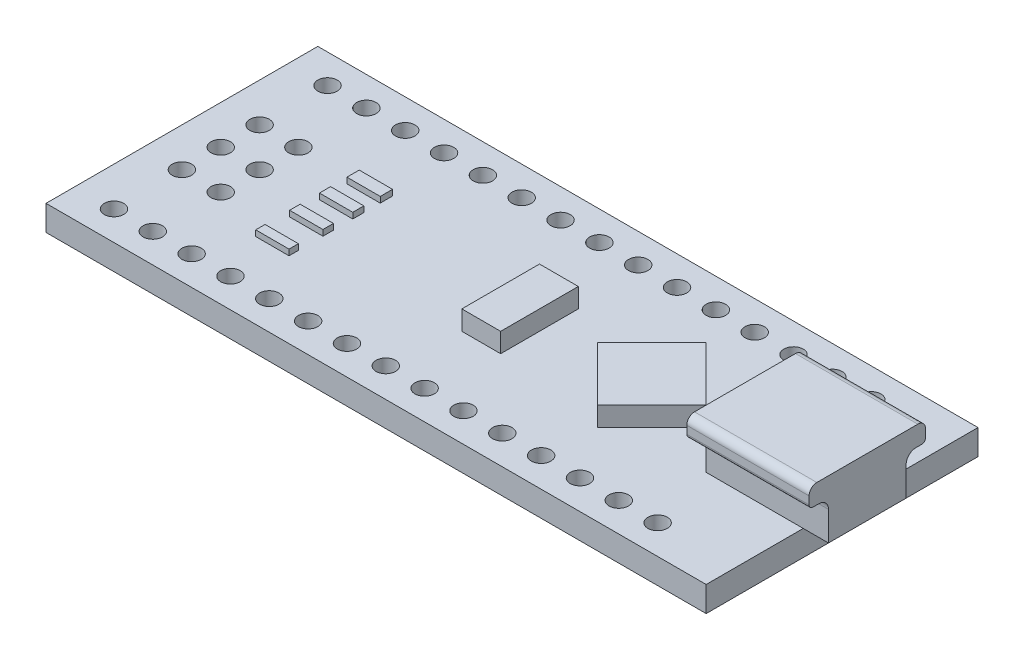
SolidWorks part; units mm, degrees
ref_plane "Front Plane" through (0, 0, 0) normal (0, 0, 1) x (1, 0, 0)
ref_plane "Top Plane" through (0, 0, 0) normal (0, 1, 0) x (1, 0, 0)
ref_plane "Right Plane" through (0, 0, 0) normal (1, 0, 0) x (0, 0, -1)
sketch "Sketch1" plane through (0, 0, 0) normal (0, 1, 0) x (1, 0, 0)
  line L1 (0, 0) -> (43.18, 0)
  line L2 (0, 0) -> (0, 17.78)
  line L3 (0, 17.78) -> (43.18, 17.78)
  line L4 (43.18, 0) -> (43.18, 17.78)
  dimension "D1" = 17.78
  dimension "D2" = 43.18
extrude "Boss-Extrude1" add sketch "Sketch1" along normal blind 1.651
sketch "Sketch2" plane through (0, 1.651, 0) normal (0, 1, 0) x (1, 0, 0)
  line L0 (0, 0) -> (43.18, 0) construction
  line L1 (0, 17.78) -> (0, 0) construction
  line L2 (0, 8.89) -> (5.9899, 8.89) construction
  circle A0 centre (2.54, 1.905) radius 0.635
  circle A1 centre (5.08, 1.905) radius 0.635
  circle A2 centre (7.62, 1.905) radius 0.635
  circle A3 centre (10.16, 1.905) radius 0.635
  circle A4 centre (12.7, 1.905) radius 0.635
  circle A5 centre (15.24, 1.905) radius 0.635
  circle A6 centre (17.78, 1.905) radius 0.635
  circle A7 centre (20.32, 1.905) radius 0.635
  circle A8 centre (22.86, 1.905) radius 0.635
  circle A9 centre (25.4, 1.905) radius 0.635
  circle A10 centre (27.94, 1.905) radius 0.635
  circle A11 centre (30.48, 1.905) radius 0.635
  circle A12 centre (33.02, 1.905) radius 0.635
  circle A13 centre (35.56, 1.905) radius 0.635
  circle A14 centre (38.1, 1.905) radius 0.635
  circle A15 centre (38.1, 15.875) radius 0.635
  circle A16 centre (35.56, 15.875) radius 0.635
  circle A17 centre (33.02, 15.875) radius 0.635
  circle A18 centre (30.48, 15.875) radius 0.635
  circle A19 centre (27.94, 15.875) radius 0.635
  circle A20 centre (25.4, 15.875) radius 0.635
  circle A21 centre (22.86, 15.875) radius 0.635
  circle A22 centre (20.32, 15.875) radius 0.635
  circle A23 centre (17.78, 15.875) radius 0.635
  circle A24 centre (15.24, 15.875) radius 0.635
  circle A25 centre (12.7, 15.875) radius 0.635
  circle A26 centre (10.16, 15.875) radius 0.635
  circle A27 centre (7.62, 15.875) radius 0.635
  circle A28 centre (5.08, 15.875) radius 0.635
  circle A29 centre (2.54, 15.875) radius 0.635
  dimension "D1" = 1.27
  dimension "D2" = 1.905
  dimension "D3" = 2.54
  dimension "D4" = 15
extrude "Cut-Extrude1" cut sketch "Sketch2" against normal through all
sketch "Sketch3" plane through (43.18, 0, 0) normal (1, 0, 0) x (0, 0, -1)
  line L0 (0, 1.651) -> (17.78, 1.651) construction
  line L1 (6.35, 1.651) -> (11.43, 1.651)
  line L2 (6.35, 1.651) -> (6.35, 3.556)
  line L3 (8.89, 1.651) -> (8.89, 0) construction
  line L4 (11.43, 1.651) -> (11.43, 3.556)
  line L5 (12.065, 4.191) -> (12.446, 4.191)
  line L6 (5.334, 4.191) -> (5.715, 4.191)
  line L7 (5.08, 4.445) -> (5.08, 4.953)
  line L8 (5.588, 5.461) -> (12.192, 5.461)
  line L9 (12.7, 4.445) -> (12.7, 4.953)
  line L10 (0, 0) -> (17.78, 0) construction
  arc A0 (12.065, 4.191) -> (11.43, 3.556) centre (12.065, 3.556) ccw
  arc A1 (6.35, 3.556) -> (5.715, 4.191) centre (5.715, 3.556) ccw
  arc A2 (12.446, 4.191) -> (12.7, 4.445) centre (12.446, 4.445) ccw
  arc A3 (5.334, 4.191) -> (5.08, 4.445) centre (5.334, 4.445) cw
  arc A4 (12.192, 5.461) -> (12.7, 4.953) centre (12.192, 4.953) cw
  arc A5 (5.08, 4.953) -> (5.588, 5.461) centre (5.588, 4.953) cw
  point P18 (6.35, 4.191)
  point P23 (5.08, 4.191)
  point P26 (12.7, 5.461)
  point P29 (5.08, 5.461)
  dimension "D6" = 0.635
  dimension "D7" = 0.254
  dimension "D8" = 0.508
  dimension "D1" = 5.08
  dimension "D2" = 7.62
  dimension "D3" = 1.27
  dimension "D4" = 2.54
  dimension "D5" = 1.27
extrude "Boss-Extrude2" add sketch "Sketch3" along normal blind 1.651 and the other way blind 6.35
sketch "Sketch4" plane through (0, 1.651, 0) normal (0, 1, 0) x (1, 0, 0)
  line L0 (27.1985, 8.89) -> (30.7443, 12.4357)
  line L1 (20.8485, 11.43) -> (23.3885, 11.43)
  line L2 (20.8485, 11.43) -> (20.8485, 6.35)
  line L3 (20.8485, 6.35) -> (23.3885, 6.35)
  line L4 (23.3885, 11.43) -> (23.3885, 6.35)
  line L5 (30.7443, 12.4357) -> (34.29, 8.89)
  line L6 (34.29, 8.89) -> (30.7443, 5.3443)
  line L7 (30.7443, 5.3443) -> (27.1985, 8.89)
  line L8 (27.1985, 8.89) -> (0, 8.89) construction
  line L9 (0, 17.78) -> (0, 0) construction
  line L10 (27.1985, 8.89) -> (34.29, 8.89) construction
  line L11 (36.83, 12.192) -> (36.83, 5.588) construction
  point P13 (36.83, 8.89)
  point P14 (27.1985, 8.89)
  point P15 (20.8485, 8.89)
  dimension "D1" = 2.54
  dimension "D2" = 3.81
  dimension "D3" = 2.54
  dimension "D4" = 5.08
extrude "Boss-Extrude3" add sketch "Sketch4" along normal blind 1.27
sketch "Sketch5" plane through (0, 1.651, 0) normal (0, 1, 0) x (1, 0, 0)
  line L0 (2.54, 8.89) -> (0, 8.89) construction
  line L1 (0, 17.78) -> (0, 0) construction
  line L2 (5.08, 8.89) -> (2.54, 8.89) construction
  circle A0 centre (2.54, 8.89) radius 0.635
  circle A1 centre (5.08, 8.89) radius 0.635
  circle A2 centre (5.08, 8.89) radius 0.635
  circle A3 centre (5.08, 11.43) radius 0.635
  circle A4 centre (2.54, 11.43) radius 0.635
  circle A5 centre (5.08, 8.89) radius 0.635
  circle A6 centre (5.08, 6.35) radius 0.635
  circle A7 centre (2.54, 6.35) radius 0.635
  dimension "D1" = 1.27
  dimension "D2" = 2.54
  dimension "D3" = 2.54
  dimension "D4" = 2
  dimension "D5" = 2
  dimension "D6" = 2
  dimension "D7" = 2
extrude "Cut-Extrude2" cut sketch "Sketch5" against normal through all contours A4 | A3 | A1 | A0 | A7 | A6
sketch "Sketch6" plane through (0, 1.651, 0) normal (0, 1, 0) x (1, 0, 0)
  line L1 (8.7403, 11.746) -> (10.9205, 11.746)
  line L2 (8.7403, 11.746) -> (8.7403, 10.9427)
  line L3 (8.7403, 10.9427) -> (10.9205, 10.9427)
  line L4 (10.9205, 11.746) -> (10.9205, 10.9427)
  line L5 (8.7403, 9.8717) -> (10.9205, 9.8717)
  line L6 (8.7403, 9.8717) -> (8.7403, 9.1449)
  line L7 (8.7403, 9.1449) -> (10.9205, 9.1449)
  line L8 (10.9205, 9.8717) -> (10.9205, 9.1449)
  line L9 (8.7403, 7.8827) -> (10.9205, 7.8827)
  line L10 (8.7403, 7.8827) -> (8.7403, 7.1942)
  line L11 (8.7403, 7.1942) -> (10.9205, 7.1942)
  line L12 (10.9205, 7.8827) -> (10.9205, 7.1942)
  line L13 (8.7403, 5.5876) -> (10.9205, 5.5876)
  line L14 (8.7403, 5.5876) -> (8.7403, 4.9756)
  line L15 (8.7403, 4.9756) -> (10.9205, 4.9756)
  line L16 (10.9205, 5.5876) -> (10.9205, 4.9756)
extrude "Boss-Extrude4" add sketch "Sketch6" along normal blind 0.381
